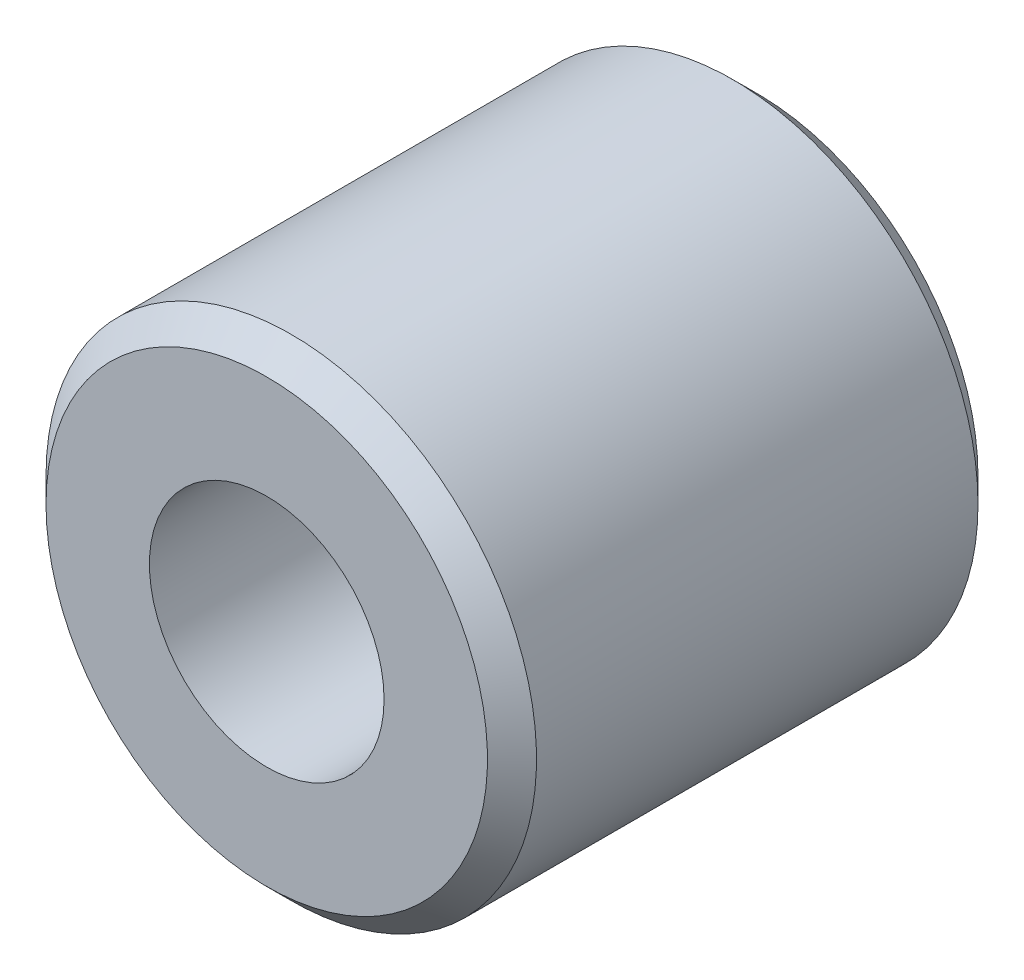
SolidWorks part; units mm, degrees
ref_plane "Front" through (0, 0, 0) normal (0, 0, 1) x (1, 0, 0)
ref_plane "Top" through (0, 0, 0) normal (0, 1, 0) x (1, 0, 0)
ref_plane "Right" through (0, 0, 0) normal (1, 0, 0) x (0, 0, -1)
sketch "Sketch1" plane through (0, 0, 0) normal (0, 0, 1) x (1, 0, 0)
  circle A0 centre (0, 0) radius 3.9688
  dimension "D1" = 7.9375
extrude "Extrude1" add sketch "Sketch1" along normal blind 7.9375
cosmetic thread "Cosmetic Thread1" parameters "D2"=7.112
chamfer "Chamfer1" distance 0.3969 angle 45 2 edges at (3.9688, 0, 7.9375) (3.9688, 0, 0)
hole_wizard "#10-24 Tapped Hole1" positions "Sketch3" profile "Sketch2" tap size "#10-24" standard "Ansi Inch" end condition through all
sketch "Sketch3" plane through (0, 0, 7.9375) normal (0, 0, 1) x (1, 0, 0)
  point P0 (0, 0)
sketch "Sketch2" plane through (0, 0, 7.9375) normal (1, 0, 0) x (0, -1, 0)
  line L0 (0, 0) -> (0, 7.9375)
  line L1 (0, 7.9375) -> (1.8986, 7.9375)
  line L2 (1.8986, 7.9375) -> (1.8986, 0)
  line L5 (1.8986, 0) -> (0, 0)
  line L11 (0, -6.35) -> (0, 107.95) construction
  dimension "Thru Tap Drill Dia." = 3.7973
  dimension "Thru Tap Drill Depth" = 7.9375
cosmetic thread "Hole Thread1"
